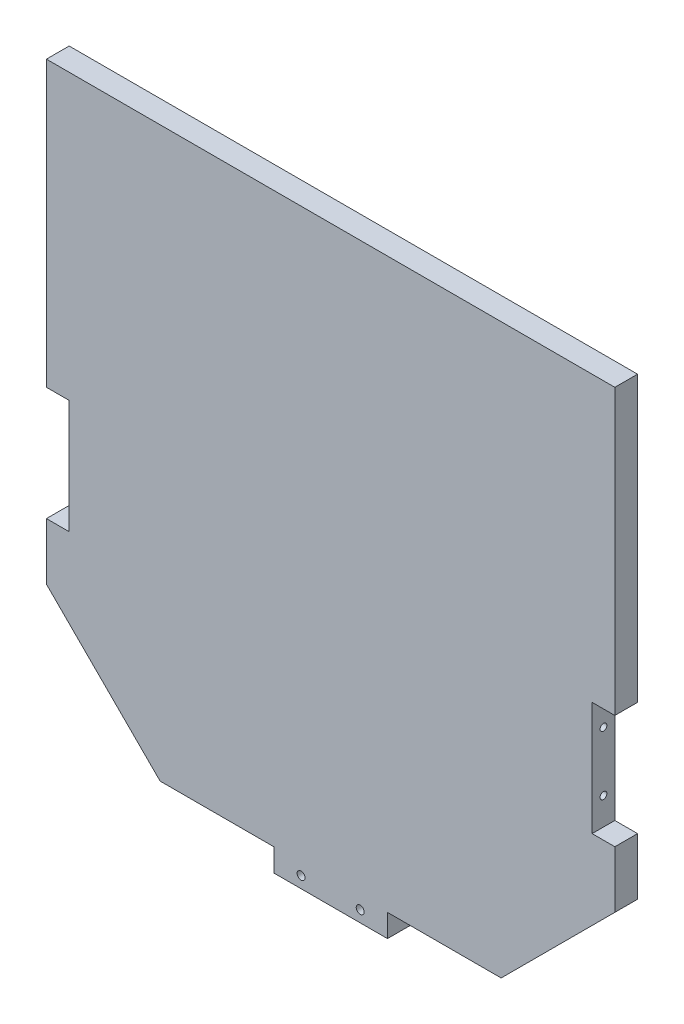
SolidWorks part; units mm, degrees
material "ABS PC"
ref_plane "Спереди" through (0, 0, 0) normal (0, 0, 1) x (1, 0, 0)
ref_plane "Сверху" through (0, 0, 0) normal (0, 1, 0) x (1, 0, 0)
ref_plane "Справа" through (0, 0, 0) normal (1, 0, 0) x (0, 0, -1)
sketch "Sketch1" plane through (0, 0, 0) normal (0, 0, 1) x (1, 0, 0)
  line L0 (-125, 75) -> (-125, 50)
  line L1 (-115, 75) -> (-115, 125)
  line L2 (0, 250) -> (0, 0) construction
  line L3 (-75, 0) -> (-25, 0)
  line L4 (-125, 75) -> (-115, 75)
  line L5 (-115, 125) -> (-125, 125)
  line L6 (-125, 125) -> (-125, 250)
  line L7 (-125, 250) -> (125, 250)
  line L8 (-125, 50) -> (-125, 0) construction
  line L9 (-125, 0) -> (-75, 0) construction
  line L10 (-25, 0) -> (25, 0) construction
  line L11 (125, 0) -> (75, 0) construction
  line L12 (125, 50) -> (125, 0) construction
  line L13 (125, 50) -> (75, 0)
  line L14 (25, 0) -> (25, -10)
  line L15 (125, 125) -> (125, 250)
  line L16 (-25, 0) -> (-25, -10)
  line L17 (-25, -10) -> (25, -10)
  line L18 (115, 125) -> (125, 125)
  line L19 (125, 75) -> (115, 75)
  line L20 (75, 0) -> (25, 0)
  line L21 (115, 75) -> (115, 125)
  line L22 (125, 75) -> (125, 50)
  line L29 (-125, 50) -> (-75, 0)
  circle A0 centre (-13, -5) radius 1.75
  circle A1 centre (13, -5) radius 1.75
  point P16 (0, -10)
  dimension "D9" = 12
  dimension "D10" = 12
  dimension "D11" = 3.5
  dimension "D12" = 5
  dimension "D1" = 250
  dimension "D2" = 125
  dimension "D3" = 25
  dimension "D4" = 50
  dimension "D5" = 50
  dimension "D6" = 75
  dimension "D7" = 50
  dimension "D8" = 10
extrude "Boss-Extrude1" add sketch "Sketch1" along normal blind 10
sketch "Sketch2" plane through (115, 0, 0) normal (1, 0, 0) x (0, 0, -1)
  line L0 (0, 75) -> (0, 125) construction
  line L1 (-10, 75) -> (0, 75) construction
  line L2 (-10, 125) -> (0, 125) construction
  circle A0 centre (-5, 113) radius 1.5
  circle A1 centre (-5, 87) radius 1.5
  dimension "D1" = 3
  dimension "D3" = 12
  dimension "D4" = 12
  dimension "D2" = 5
extrude "Cut-Extrude1" cut sketch "Sketch2" against normal blind 15
mirror "Mirror1" about plane through (0, 0, 0) normal (1, 0, 0) of "Cut-Extrude1"
